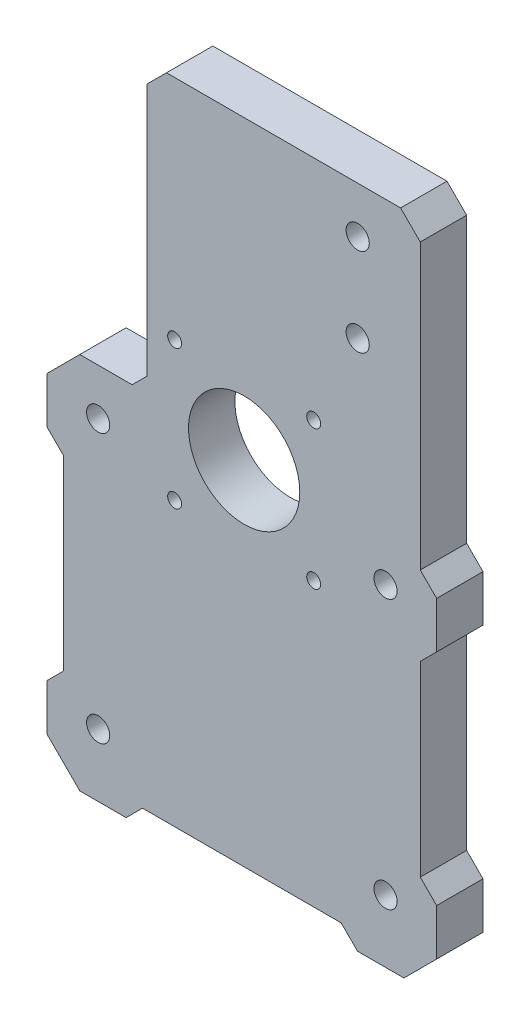
SolidWorks part; units mm, degrees
ref_plane "Alzado" through (0, 0, 0) normal (0, 0, 1) x (1, 0, 0)
ref_plane "Planta" through (0, 0, 0) normal (0, 1, 0) x (1, 0, 0)
ref_plane "Vista lateral" through (0, 0, 0) normal (1, 0, 0) x (0, 0, -1)
sketch "Croquis1" plane through (0, 0, 0) normal (0, 0, 1) x (1, 0, 0)
  line L0 (0, 0) -> (0, 36.5) construction
  line L5 (31, 29) -> (-31, 29)
  line L10 (31, 29) -> (31, -29)
  line L11 (31, -29) -> (-31, -29)
  line L12 (-31, 29) -> (-31, -29)
  line L13 (31, 29) -> (-31, -29) construction
  line L14 (31, -29) -> (-31, 29) construction
  line L15 (-38.5, 39) -> (-20.5, 39)
  line L16 (-38.5, 39) -> (-38.5, -39)
  line L17 (-38.5, -39) -> (38.5, -39)
  line L18 (38.5, 39) -> (38.5, -39)
  line L19 (-38.5, 39) -> (38.5, -39) construction
  line L20 (-38.5, -39) -> (38.5, 39) construction
  line L21 (38.5, 39) -> (38.5, 96.7574)
  line L26 (34.2574, 101) -> (-16.2574, 101)
  line L27 (-20.5, 96.7574) -> (-20.5, 39)
  line L28 (34.2574, 101) -> (38.5, 96.7574)
  line L29 (-16.2574, 101) -> (-20.5, 96.7574)
  circle A0 centre (-31, 29) radius 2.5
  circle A1 centre (31, 29) radius 2.5
  circle A2 centre (31, -29) radius 2.5
  circle A3 centre (-31, -29) radius 2.5
  point P0 (0, 0)
  point P5 (0, 0)
  dimension "D5" = 36.5
  dimension "D6" = 62
  dimension "D1" = 62
  dimension "D2" = 58
  dimension "D3" = 78
  dimension "D4" = 77
  dimension "D7" = 59
  dimension "D8" = 135
  dimension "D9" = 6
  dimension "D10" = 45
  dimension "D11" = 6
extrude "Saliente-Extruir1" add sketch "Croquis1" along normal blind 10 contours L26 L29 L27 L15 L16 L17 L18 L21 L28 A3 L12 A0 L5 A1 L10 A2 L11 | A3 L11 A2 L10 A1 L5 A0 L12
sketch "Croquis9" plane through (0, 0, 10) normal (0, 0, 1) x (1, 0, 0)
  line L0 (21.4289, -39) -> (24.9645, -42.5355)
  line L1 (-38.5, -39) -> (38.5, -39) construction
  line L2 (24.9645, -42.5355) -> (34.9645, -42.5355)
  line L3 (34.9645, -42.5355) -> (42.0355, -35.4645)
  line L4 (42.0355, -35.4645) -> (42.0355, -25.4645)
  line L5 (42.0355, -25.4645) -> (38.5, -21.9289)
  line L6 (38.5, 96.7574) -> (38.5, -39) construction
  line L7 (0, -5.5) -> (0, 5.5) construction
  line L8 (-42.0355, -25.4645) -> (-38.5, -21.9289)
  line L9 (-42.0355, -35.4645) -> (-42.0355, -25.4645)
  line L10 (-34.9645, -42.5355) -> (-42.0355, -35.4645)
  line L11 (-24.9645, -42.5355) -> (-34.9645, -42.5355)
  line L12 (-21.4289, -39) -> (-24.9645, -42.5355)
  line L13 (-38.5, -21.9289) -> (-38.5, -30.4645)
  line L14 (-29.9645, -39) -> (-21.4289, -39)
  line L15 (-29.9645, -39) -> (-38.5, -30.4645)
  line L16 (38.5, -21.9289) -> (38.5, -30.4645)
  line L17 (29.9645, -39) -> (21.4289, -39)
  line L18 (29.9645, -39) -> (38.5, -30.4645)
  line L19 (-38.5, 39) -> (-20.5, 39) construction
  line L21 (-23.668, 39) -> (-20.1325, 42.5355)
  line L22 (-34.9645, 39) -> (-42.0355, 31.9289)
  line L23 (-42.0355, 31.9289) -> (-42.0355, 21.9289)
  line L24 (-42.0355, 21.9289) -> (-38.5, 18.3934)
  line L25 (-38.5, 39) -> (-38.5, -39) construction
  line L26 (42.0355, 21.9289) -> (38.5, 18.3934)
  line L27 (42.0355, 31.9289) -> (42.0355, 21.9289)
  line L28 (34.9645, 39) -> (42.0355, 31.9289)
  line L29 (-34.9645, 39) -> (-38.5, 18.3934)
  line L30 (38.5, 18.3934) -> (34.9645, 39)
  line M29 (-20.5, 96.7574) -> (-20.5, 39)
  line M30 (-20.5, 39) -> (-38.5, 39)
  line M31 (-38.5, 39) -> (-38.5, -39)
  line M32 (-38.5, -39) -> (38.5, -39)
  line M33 (38.5, -39) -> (38.5, 96.7574)
  dimension "D1" = 45
  dimension "D2" = 45
  dimension "D3" = 10
  dimension "D4" = 10
  dimension "D5" = 10
  dimension "D6" = 5
  dimension "D7" = 5
  dimension "D8" = 45
  dimension "D10" = 10
  dimension "D12" = 10
  dimension "D13" = 135
  dimension "D14" = 5
extrude "Saliente-Extruir2" add sketch "Croquis9" against normal through all contours L29 L22 M31 | L23 L24 L22 M31 | L30 L28 M33 | L28 L26 L27 M33 | L4 L5 L3 M33 | L2 L3 L0 M32 | L18 M32 M33 | L10 L8 L9 M31 | L15 M32 M31 | L12 L10 L11 M32 | L21 M30 M29
sketch "Croquis10" plane through (0, 0, 10) normal (0, 0, 1) x (1, 0, 0)
  line L0 (-38.5, 35.4645) -> (-34.9645, 39)
  line L1 (-38.5, 39) -> (-23.668, 39) construction
  line L2 (-34.9645, 39) -> (-38.5, 39)
  line L3 (-38.5, 39) -> (-38.5, 35.4645)
  line L4 (38.5, 91) -> (25, 91) construction
  line L5 (38.5, 96.7574) -> (38.5, 35.4645) construction
  line L6 (34.2574, 101) -> (-16.2574, 101) construction
  line L7 (-38.5, 18.3934) -> (-38.5, -21.9289) construction
  line L8 (-21.4289, -39) -> (21.4289, -39) construction
  line L10 (-14.5, 52) -> (15.5, 52)
  line L11 (-14.5, 52) -> (-14.5, 22)
  line L12 (-14.5, 22) -> (15.5, 22)
  line L13 (15.5, 52) -> (15.5, 22)
  line L14 (-14.5, 52) -> (15.5, 22) construction
  line L15 (-14.5, 22) -> (15.5, 52) construction
  circle A0 centre (25, 91) radius 2.5
  circle A2 centre (25, 72) radius 2.5
  circle A3 centre (0.5, 37) radius 12
  circle A4 centre (-14.5, 52) radius 1.5
  circle A5 centre (15.5, 52) radius 1.5
  circle A6 centre (15.5, 22) radius 1.5
  circle A7 centre (-14.5, 22) radius 1.5
  line M22 (-23.668, 39) -> (-38.5, 39)
  line M23 (-38.5, 39) -> (-38.5, 35.4645)
  dimension "D1" = 13.5
  dimension "D2" = 5
  dimension "D3" = 10
  dimension "D5" = 24
  dimension "D8" = 2
  dimension "D6" = 39
  dimension "D7" = 76
  dimension "D9" = 2
  dimension "D4" = 2
extrude "Cortar-Extruir1" cut sketch "Croquis10" against normal through all contours L0 M23 M22 | A2 | A0 | A3 | A4 | A5 | A6 | A7
